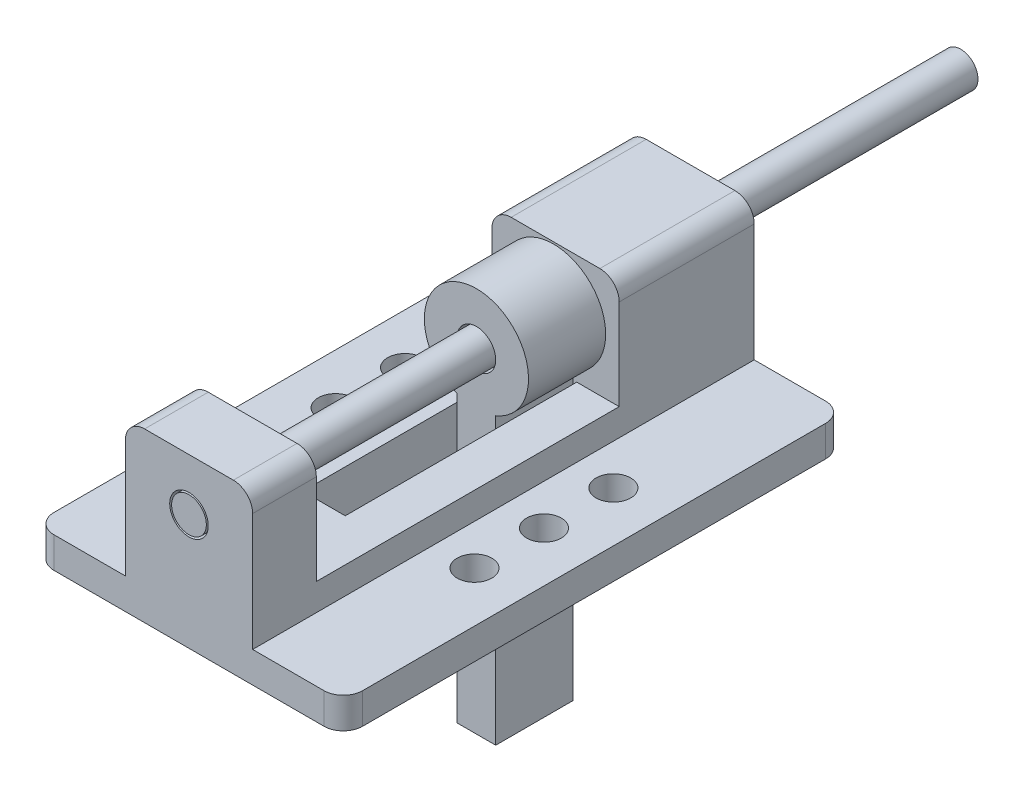
SolidWorks part; units mm, degrees
ref_plane "Ön Düzlem" through (0, 0, 0) normal (0, 0, 1) x (1, 0, 0)
ref_plane "Üst Düzlem" through (0, 0, 0) normal (0, 1, 0) x (1, 0, 0)
ref_plane "Sağ Düzlem" through (0, 0, 0) normal (1, 0, 0) x (0, 0, -1)
sketch "Çizim1" plane through (0, 0, 0) normal (0, 1, 0) x (1, 0, 0)
  line L1 (-8, -13) -> (8, -13)
  line L2 (-8, -13) -> (-8, 13)
  line L3 (-8, 13) -> (8, 13)
  line L4 (8, -13) -> (8, 13)
  line L5 (0, 13) -> (0, -13) construction
  line L6 (-8, 0) -> (8, 0) construction
  line L7 (-1.1, 6) -> (1.1, 6)
  line L8 (-1.1, 6) -> (-1.1, -6)
  line L9 (-1.1, -6) -> (1.1, -6)
  line L10 (1.1, 6) -> (1.1, -6)
  circle A0 centre (5.4, 0) radius 0.9
  circle A1 centre (5.4, 3.6) radius 0.9
  circle A2 centre (5.4, -3.6) radius 0.9
  circle A3 centre (-5.4, 3.6) radius 0.9
  circle A4 centre (-5.4, -3.6) radius 0.9
  circle A5 centre (-5.4, 0) radius 0.9
  point P0 (0, 0)
  point P11 (0, 6)
  dimension "D3" = 1.8
  dimension "D1" = 26
  dimension "D2" = 16
  dimension "D4" = 5.4
  dimension "D5" = 3.6
  dimension "D6" = 7
  dimension "D7" = 12
  dimension "D8" = 2.2
extrude "Yükseklik-Ekstrüzyon1" add sketch "Çizim1" against normal blind 1.6
sketch "Çizim2" plane through (0, 0, 0) normal (0, 1, 0) x (1, 0, 0)
  line L0 (8, 13) -> (-8, 13) construction
  line L1 (-3.3, 13) -> (3.3, 13)
  line L2 (-3.3, 13) -> (-3.3, -13)
  line L3 (-3.3, -13) -> (3.3, -13)
  line L4 (3.3, 13) -> (3.3, -13)
  line L5 (-8, -13) -> (8, -13) construction
  line L6 (-1.1, -6) -> (1.1, -6) construction
  line L7 (1.1, 6) -> (-1.1, 6) construction
  line L8 (-1.1, 6) -> (-1.1, -6) construction
  line L9 (1.1, -6) -> (1.1, 6) construction
  line L10 (-1.1, -6) -> (1.1, -6)
  line L11 (1.1, 6) -> (-1.1, 6)
  line L12 (-1.1, 6) -> (-1.1, -6)
  line L13 (1.1, -6) -> (1.1, 6)
  point P9 (0, 13)
  dimension "D1" = 6.6
extrude "Yükseklik-Ekstrüzyon2" add sketch "Çizim2" along normal blind 1.4
sketch "Çizim3" plane through (0, 0, -13) normal (0, 0, -1) x (-1, 0, 0)
  line L0 (3.3, 1.4) -> (3.3, 0) construction
  line L1 (-3.3, 1.4) -> (3.3, 1.4)
  line L2 (-3.3, 1.4) -> (-3.3, 7.1)
  line L3 (-3.3, 7.1) -> (3.3, 7.1)
  line L4 (3.3, 1.4) -> (3.3, 7.1)
  line L5 (-8, -1.6) -> (8, -1.6) construction
  dimension "D1" = 8.7
extrude "Yükseklik-Ekstrüzyon3" add sketch "Çizim3" against normal blind 7
sketch "Çizim4" plane through (0, 0, 13) normal (0, 0, 1) x (1, 0, 0)
  line L8 (1.1, -1.6) -> (1.1, 1.4)
  line L9 (1.1, 1.4) -> (3.3, 1.4)
  line L10 (3.3, 1.4) -> (3.3, 7.1)
  line L11 (3.3, 7.1) -> (-3.3, 7.1)
  line L12 (-3.3, 7.1) -> (-3.3, 1.4)
  line L13 (-3.3, 1.4) -> (-1.1, 1.4)
  line L14 (-1.1, 1.4) -> (-1.1, -1.6)
  line L15 (-1.1, -1.6) -> (1.1, -1.6)
  line L16 (1.1, -1.6) -> (1.1, 1.4)
  line L17 (1.1, 1.4) -> (3.3, 1.4)
  line L18 (3.3, 1.4) -> (3.3, 7.1)
  line L19 (3.3, 7.1) -> (-3.3, 7.1)
  line L20 (-3.3, 7.1) -> (-3.3, 1.4)
  line L21 (-3.3, 1.4) -> (-1.1, 1.4)
  line L22 (-1.1, 1.4) -> (-1.1, -1.6)
  line L23 (-1.1, -1.6) -> (1.1, -1.6)
  dimension "D1" = 0
extrude "Yükseklik-Ekstrüzyon4" add sketch "Çizim4" against normal blind 3.3
sketch "Çizim5" plane through (0, 0, -13) normal (0, 0, -1) x (-1, 0, 0)
  line L0 (-8, -1.6) -> (8, -1.6) construction
  circle A0 centre (0, 4.4) radius 1
  point P2 (0, 0)
  dimension "D1" = 6
  dimension "D2" = 2
extrude "Kes-Ekstrüzyon1" cut sketch "Çizim5" against normal through all
fillet "Radyus1" radius 1 4 edges at (3.3, 7.1, 11.35) (-3.3, 7.1, 11.35) (-3.3, 7.1, -9.5) (3.3, 7.1, -9.5)
sketch "Çizim6" plane through (0, 0, -6) normal (0, 0, 1) x (1, 0, 0)
  line L0 (2.3, 7.1) -> (-2.3, 7.1) construction
  circle A0 centre (0, 4.4) radius 2.7
  circle A1 centre (0, 4.4) radius 1
  circle A2 centre (0, 4.4) radius 1 construction
extrude "Yükseklik-Ekstrüzyon5" add sketch "Çizim6" along normal blind 4 from offset 0.1 separate body
sketch "Çizim7" plane through (0, 0, -1.9) normal (0, 0, 1) x (1, 0, 0)
  line L1 (-1, 4.4) -> (1, 4.4)
  line L2 (-1, 4.4) -> (-1, -12.9)
  line L3 (-1, -12.9) -> (1, -12.9)
  line L4 (1, 4.4) -> (1, -12.9)
  circle A0 centre (0, 4.4) radius 1 construction
  circle A1 centre (0, 4.4) radius 1 construction
  circle A2 centre (0, 4.4) radius 2.7 construction
  circle A3 centre (0, 4.4) radius 2.7
  point P12 (0, 7.1)
  circle M3 centre (0, 4.4) radius 2.7
  circle M4 centre (0, 4.4) radius 1
  dimension "D1" = 2
  dimension "D2" = 20
extrude "Yükseklik-Ekstrüzyon6" add sketch "Çizim7" against normal blind 4 contours L4 L2 M4 M3 | L4 L2 L3 M3
sketch "Çizim8" plane through (0, 0, 13) normal (0, 0, 1) x (1, 0, 0)
  circle A0 centre (0, 4.4) radius 0.9
  point P0 (0, 4.4)
  dimension "D1" = 1.8
extrude "Yükseklik-Ekstrüzyon7" add sketch "Çizim8" against normal offset from surface (40 mm away) 14 separate body up to face at (-1, 4.4, -13) offset beyond the face yes
fillet "Radyus2" radius 1 4 edges at (8, -0.8, 13) (-8, -0.8, 13) (-8, -0.8, -13) (8, -0.8, -13)
